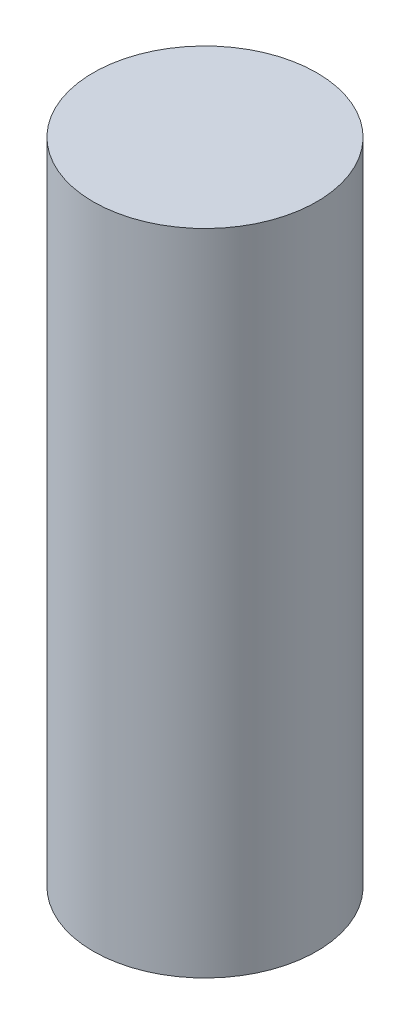
SolidWorks part; units mm, degrees
ref_plane "Front Plane" through (0, 0, 0) normal (0, 0, 1) x (1, 0, 0)
ref_plane "Top Plane" through (0, 0, 0) normal (0, 1, 0) x (1, 0, 0)
ref_plane "Right Plane" through (0, 0, 0) normal (1, 0, 0) x (0, 0, -1)
sketch "Sketch1" plane through (0, 0, 0) normal (0, 1, 0) x (1, 0, 0)
  circle A0 centre (0, 0) radius 31
  dimension "D1" = 62
extrude "Boss-Extrude1" add sketch "Sketch1" along normal blind 180
